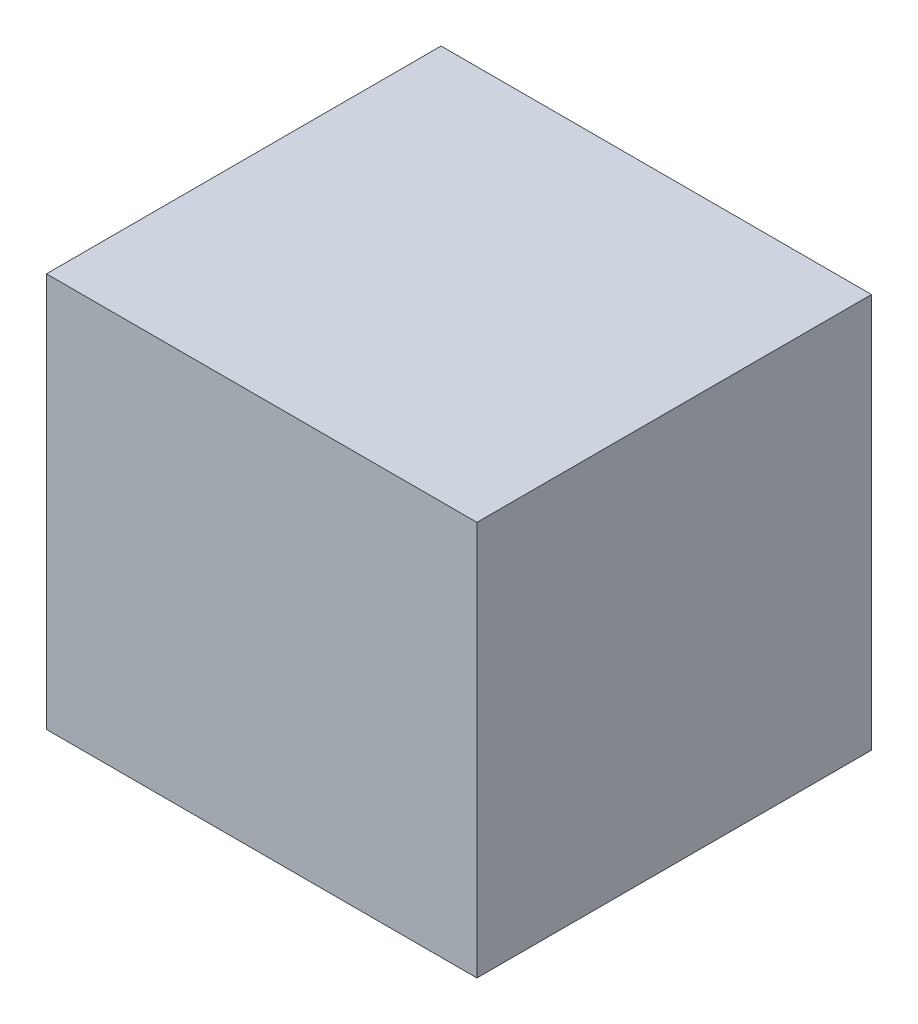
SolidWorks part; units mm, degrees
ref_plane "Front Plane" through (0, 0, 0) normal (1, 0, 0) x (0, 1, 0)
ref_plane "Top Plane" through (0, 0, 0) normal (0, 0, 1) x (0, 1, 0)
ref_plane "Right Plane" through (0, 0, 0) normal (0, 1, 0) x (-1, 0, 0)
sketch "Sketch1" plane through (0, 0, 0) normal (0, 1, 0) x (-1, 0, 0)
  line L1 (-1200, 1100) -> (1200, 1100)
  line L2 (-1200, 1100) -> (-1200, -1100)
  line L3 (-1200, -1100) -> (1200, -1100)
  line L4 (1200, 1100) -> (1200, -1100)
  line L5 (-1200, 1100) -> (1200, -1100) construction
  line L6 (-1200, -1100) -> (1200, 1100) construction
  point P0 (0, 0)
extrude "Boss-Extrude1" add sketch "Sketch1" along normal blind 2200
sketch "Sketch2" plane through (0, 0, 0) normal (0, -1, 0) x (-1, 0, 0)
  line L0 (0, -1100) -> (0, 1100) construction
  line L1 (1200, -1100) -> (-1200, -1100) construction
  line L2 (-1200, 1100) -> (1200, 1100) construction
  line L3 (1200, 0) -> (-1200, 0) construction
  line L4 (1200, 1100) -> (1200, -1100) construction
  line L5 (-1200, -1100) -> (-1200, 1100) construction
  circle A0 centre (0, 0) radius 320
  dimension "D1" = 640
extrude "Boss-Extrude2" add sketch "Sketch2" along normal blind 430
